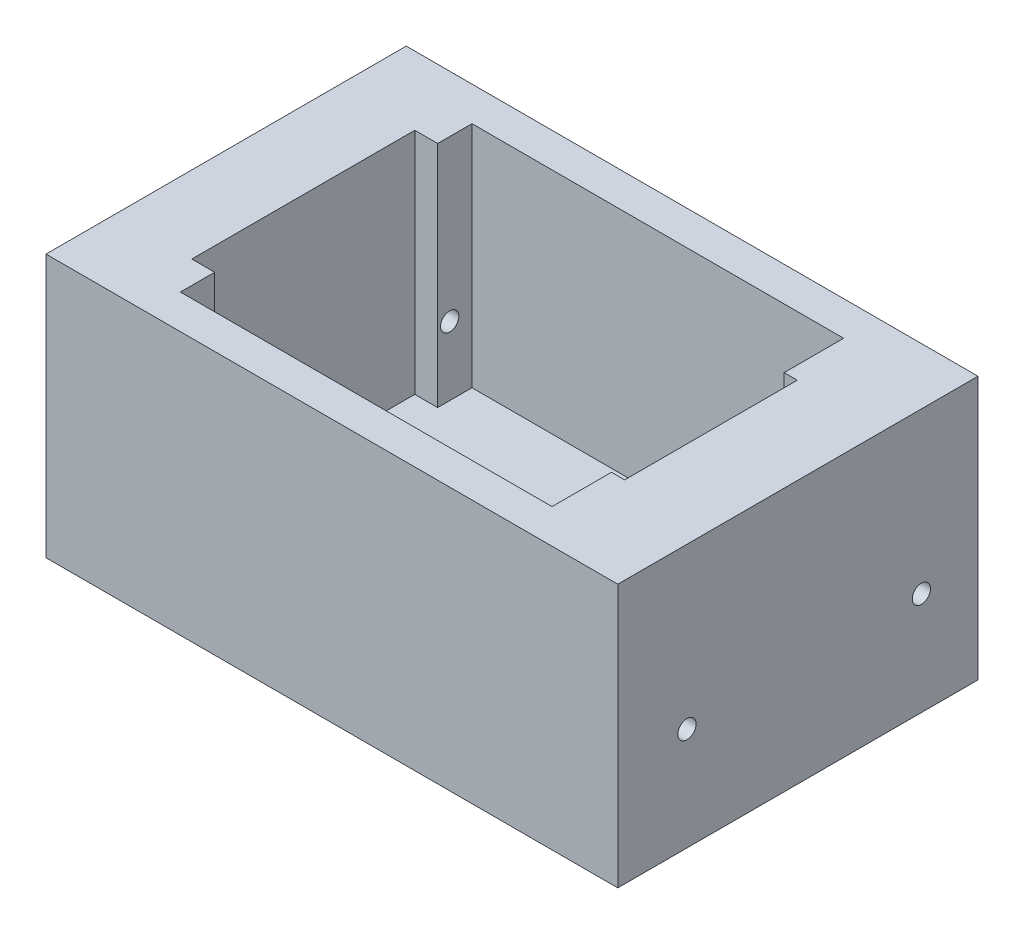
SolidWorks part; units mm, degrees
ref_plane "Front Plane" through (0, 0, 0) normal (0, 0, 1) x (1, 0, 0)
ref_plane "Top Plane" through (0, 0, 0) normal (0, 1, 0) x (1, 0, 0)
ref_plane "Right Plane" through (0, 0, 0) normal (1, 0, 0) x (0, 0, -1)
sketch "Sketch1" plane through (0, 0, 0) normal (0, 1, 0) x (1, 0, 0)
  line L1 (0, 0) -> (50, 0)
  line L2 (0, 0) -> (0, 31.5)
  line L3 (0, 31.5) -> (50, 31.5)
  line L4 (50, 0) -> (50, 31.5)
  dimension "D1" = 31.5
  dimension "D2" = 50
extrude "Boss-Extrude1" add sketch "Sketch1" along normal blind 23
sketch "Sketch2" plane through (0, 23, 0) normal (0, 1, 0) x (1, 0, 0)
  line L0 (25, 35.2211) -> (25, -2.3698) construction
  line L1 (0, 31.5) -> (0, 0) construction
  line L2 (41.25, 28.5) -> (8.75, 28.5)
  line L3 (8.75, 28.5) -> (8.75, 25.5)
  line L4 (8.75, 25.5) -> (6.75, 25.5)
  line L5 (6.75, 25.5) -> (6.75, 6)
  line L6 (6.75, 6) -> (8.75, 6)
  line L7 (8.75, 6) -> (8.75, 3)
  line L8 (8.75, 3) -> (41.25, 3)
  line L9 (41.25, 3) -> (41.25, 8.2)
  line L10 (41.25, 8.2) -> (42.4, 8.2)
  line L11 (42.4, 8.2) -> (42.4, 23.3)
  line L12 (42.4, 23.3) -> (41.25, 23.3)
  line L13 (41.25, 23.3) -> (41.25, 28.5)
  line L15 (0, 0) -> (50, 0) construction
  line L17 (50, 31.5) -> (0, 31.5) construction
  dimension "D1" = 25
  dimension "D2" = 1.15
  dimension "D3" = 2
  dimension "D4" = 3
  dimension "D5" = 19.5
  dimension "D6" = 5.2
  dimension "D7" = 15.1
  dimension "D8" = 32.5
  dimension "D9" = 3
  dimension "D11" = 3
  dimension "D12" = 3
extrude "Cut-Extrude1" cut sketch "Sketch2" against normal blind 20
sketch "Sketch3" plane through (41.25, 0, 0) normal (-1, 0, 0) x (0, 0, 1)
  line L3 (-8.2, 3) -> (-8.2, 23) construction
  line L4 (-8.2, 3) -> (-23.3, 3) construction
  line L5 (-23.3, 3) -> (-23.3, 23) construction
  line L6 (-8.2, 3) -> (-8.2, 23)
  line L7 (-8.2, 3) -> (-23.3, 3)
  line L8 (-23.3, 3) -> (-23.3, 23)
  circle A2 centre (-26.55, 9) radius 0.8
  circle A3 centre (-6.05, 9) radius 0.8
  dimension "D5" = 1.6
  dimension "D6" = 6
  dimension "D7" = 20.5
  dimension "D8" = 3.25
extrude "Cut-Extrude2" cut sketch "Sketch3" along normal through all both and the other way through all contours A2 | A3
sketch "Sketch4" plane through (8.75, 0, 0) normal (1, 0, 0) x (0, 0, -1)
  line L3 (25.5, 3) -> (25.5, 23) construction
  line L4 (25.5, 3) -> (6, 3) construction
  line L5 (6, 3) -> (6, 8.2016) construction
  line L6 (25.5, 3) -> (25.5, 23)
  line L7 (25.5, 3) -> (6, 3)
  line L8 (6, 3) -> (6, 8.2016)
  circle A2 centre (5, 5.4) radius 0.8
  circle A3 centre (25.5, 5.4) radius 0.8
  dimension "D5" = 1.6
  dimension "D6" = 20.5
  dimension "D7" = 1
  dimension "D8" = 2.4
extrude "Cut-Extrude3" [suppressed] cut sketch "Sketch4" against normal up to surface (8.75 mm away) contours A2
